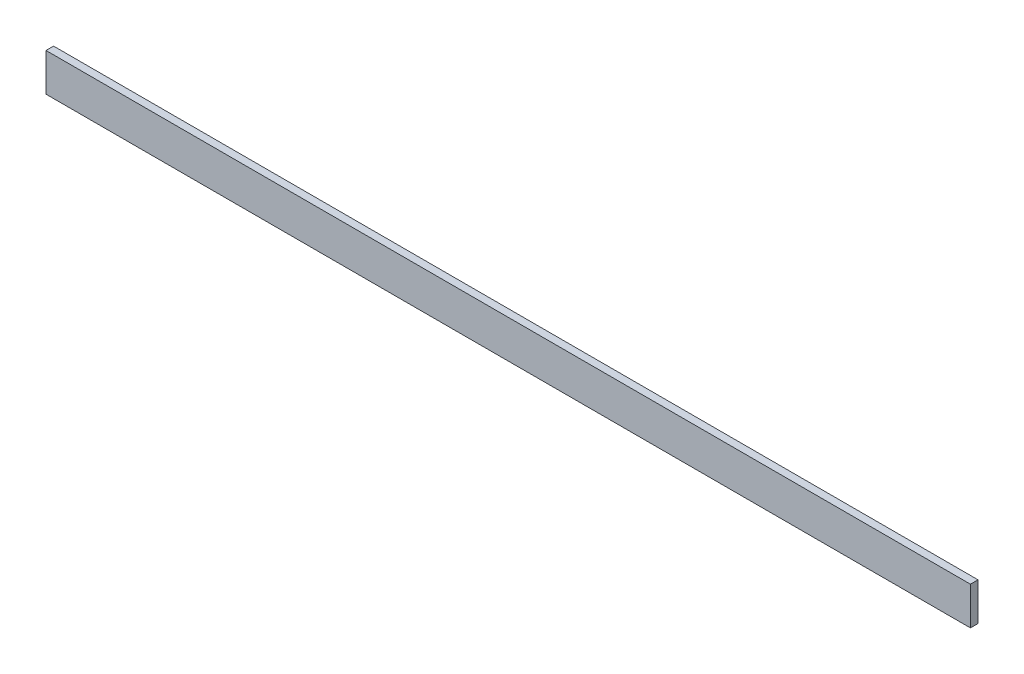
SolidWorks part; units mm, degrees
ref_plane "Front Plane" through (0, 0, 0) normal (0, 0, 1) x (1, 0, 0)
ref_plane "Top Plane" through (0, 0, 0) normal (0, 1, 0) x (1, 0, 0)
ref_plane "Right Plane" through (0, 0, 0) normal (1, 0, 0) x (0, 0, -1)
sketch "Sketch1" plane through (0, 0, 0) normal (0, 0, 1) x (1, 0, 0)
  line L1 (305, 12.5) -> (-305, 12.5)
  line L2 (305, 12.5) -> (305, -12.5)
  line L3 (305, -12.5) -> (-305, -12.5)
  line L4 (-305, 12.5) -> (-305, -12.5)
  line L5 (305, 12.5) -> (-305, -12.5) construction
  line L6 (305, -12.5) -> (-305, 12.5) construction
  point P0 (0, 0)
  dimension "D1" = 610
  dimension "D2" = 25
extrude "Boss-Extrude1" add sketch "Sketch1" along normal blind 5
